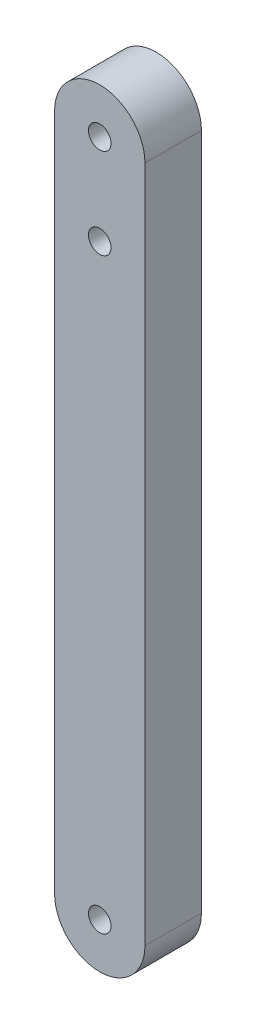
SolidWorks part; units mm, degrees
material "AISI 1020"
ref_plane "Plan de face" through (0, 0, 0) normal (0, 0, 1) x (1, 0, 0)
ref_plane "Plan de dessus" through (0, 0, 0) normal (0, 1, 0) x (1, 0, 0)
ref_plane "Plan de droite" through (0, 0, 0) normal (1, 0, 0) x (0, 0, -1)
sketch "Esquisse1" plane through (0, 0, 0) normal (0, 0, 1) x (1, 0, 0)
  line L0 (0, 0) -> (0, 120) construction
  line L1 (-8, 0) -> (-8, 120)
  line L2 (8, 0) -> (8, 120)
  arc A0 (-8, 0) -> (8, 0) centre (0, 0) ccw
  arc A1 (8, 120) -> (-8, 120) centre (0, 120) ccw
  circle A2 centre (0, 120) radius 2
  circle A3 centre (0, 0) radius 2
  circle A5 centre (0, 104) radius 2
  point P3 (0, 60)
  dimension "D1" = 120
  dimension "D2" = 16
  dimension "D3" = 4
  dimension "D4" = 8
extrude "Boss.-Extru.1" add sketch "Esquisse1" along normal blind 10
